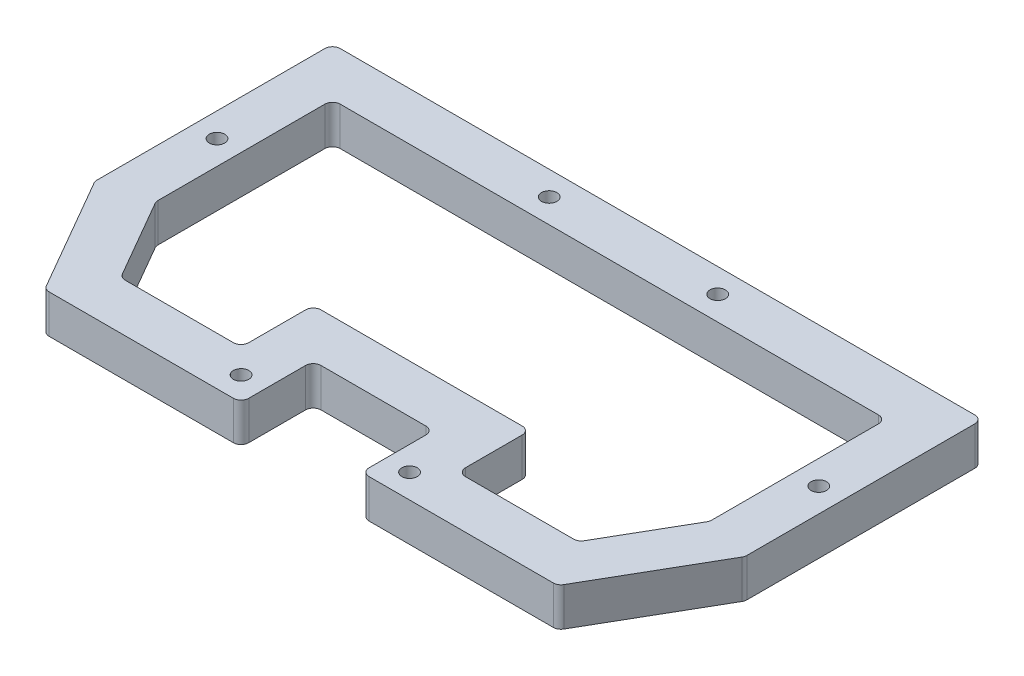
SolidWorks part; units mm, degrees
material "ABS"
ref_plane "Front" through (0, 0, 0) normal (0, 0, 1) x (1, 0, 0)
ref_plane "Top" through (0, 0, 0) normal (0, 1, 0) x (1, 0, 0)
ref_plane "Right" through (0, 0, 0) normal (1, 0, 0) x (0, 0, -1)
sketch "草图1" plane through (0, 0, 0) normal (0, 1, 0) x (1, 0, 0)
  line L0 (0, 19.25) -> (0, -26.6824) construction
  line L1 (-67.5, 74) -> (-67.5, 24.641)
  line L2 (-67.5, 24.641) -> (-53.2735, 0)
  line L3 (-53.2735, 0) -> (-12.5, 0)
  line L4 (-12.5, 0) -> (-12.5, 15)
  line L5 (-12.5, 15) -> (12.5, 15)
  line L6 (12.5, 15) -> (12.5, 0)
  line L7 (12.5, 0) -> (53.2735, 0)
  line L8 (53.2735, 0) -> (67.5, 24.641)
  line L9 (67.5, 24.641) -> (67.5, 74)
  line L10 (-57.5, 27.3205) -> (-57.5, 64)
  line L11 (-57.5, 27.3205) -> (-47.5, 10)
  line L12 (-47.5, 10) -> (-22.5, 10)
  line L13 (-22.5, 10) -> (-22.5, 25)
  line L14 (-22.5, 25) -> (22.5, 25)
  line L15 (22.5, 25) -> (22.5, 10)
  line L16 (22.5, 10) -> (47.5, 10)
  line L17 (47.5, 10) -> (57.5, 27.3205)
  line L18 (-57.5, 64) -> (57.5, 64)
  line L19 (57.5, 64) -> (57.5, 27.3205)
  line L20 (67.5, 74) -> (-67.5, 74)
  line L48 (-57.5, 74) -> (-57.5, 27.3205) construction
  line L49 (57.5, 27.3205) -> (57.5, 74) construction
  circle A0 centre (17.5, 5) radius 1.6
  circle A1 centre (-62.5, 45) radius 1.6
  circle A2 centre (17.5, 69) radius 1.6
  circle A3 centre (-17.5, 5) radius 1.6
  circle A4 centre (-17.5, 69) radius 1.6
  circle A5 centre (62.5, 45) radius 1.6
  point P12 (0, 15)
  dimension "D9" = 3.2
  dimension "D10" = 3.2
  dimension "D12" = 5
  dimension "D14" = 5
  dimension "D8" = 80
  dimension "D17" = 64
  dimension "D11" = 40
  dimension "D1" = 60
  dimension "D2" = 25
  dimension "D4" = 10
  dimension "D5" = 15
  dimension "D6" = 20
  dimension "D7" = 64
  dimension "D13" = 5
  dimension "D15" = 25
  dimension "D3" = 10
  dimension "D16" = 2
extrude "凸台-拉伸1" add sketch "草图1" along normal blind 8 contours L20 L1 L2 L3 L4 L5 L6 L7 L8 L9
fillet "圆角1" radius 1.6 20 edges at (12.5, 4, 0) (-57.5, 4, -64) (-57.5, 4, -27.3205) (-47.5, 4, -10) (-22.5, 4, -10) (22.5, 4, -25) (22.5, 4, -10) (47.5, 4, -10) (57.5, 4, -27.3205) (57.5, 4, -64) (-22.5, 4, -25) (67.5, 4, -74) (67.5, 4, -24.641) (53.2735, 4, 0) (12.5, 4, -15) (-12.5, 4, -15) (-53.2735, 4, 0) (-67.5, 4, -24.641) (-67.5, 4, -74) (-12.5, 4, 0)
